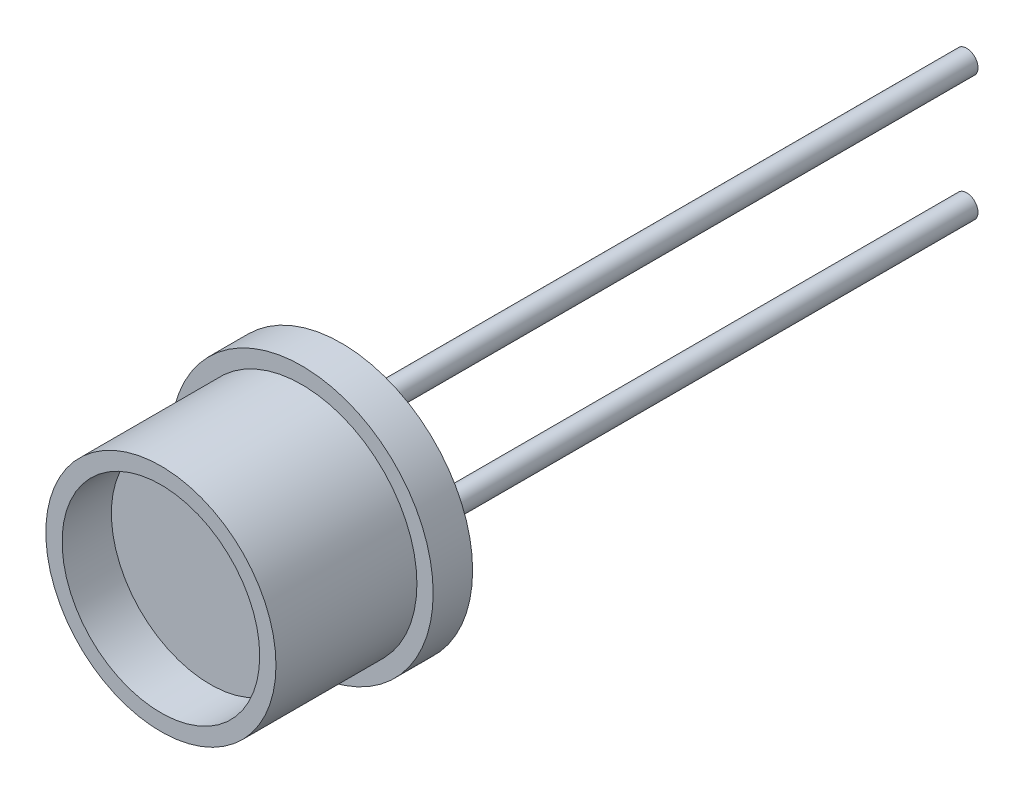
SolidWorks part; units mm, degrees
other "DetailItem1"
other "DetailItem2"
other "DetailItem3"
ref_plane "Front Plane" through (0, 0, 0) normal (0, 0, 1) x (1, 0, 0)
ref_plane "Top Plane" through (0, 0, 0) normal (0, 1, 0) x (1, 0, 0)
ref_plane "Right Plane" through (0, 0, 0) normal (1, 0, 0) x (0, 0, -1)
sketch "Sketch1" plane through (0, 0, 0) normal (0, 0, 1) x (1, 0, 0)
  circle A0 centre (0, 0) radius 2.665
  dimension "D1" = 5.33
extrude "Boss-Extrude1" add sketch "Sketch1" along normal blind 0.8
sketch "Sketch2" plane through (0, 0, 0.8) normal (0, 0, 1) x (1, 0, 0)
  circle A0 centre (0, 0) radius 2.335
  dimension "D1" = 4.67
extrude "Boss-Extrude2" add sketch "Sketch2" along normal blind 2.86
sketch "Sketch3" plane through (0, 0, 0) normal (0, 0, -1) x (-1, 0, 0)
  circle A0 centre (0, 0) radius 1.27
  circle A1 centre (0, 1.27) radius 0.23
  dimension "D1" = 2.54
  dimension "D2" = 0.46
extrude "Boss-Extrude3" add sketch "Sketch3" along normal blind 12.69 contours A1
pattern_circular "CirPattern1" count 3 every 90 about axis through (0, 0, 0) along (0, 0, 1) of "Boss-Extrude3"
sketch "Sketch4" plane through (0, 0, 3.66) normal (0, 0, 1) x (1, 0, 0)
  circle A0 centre (0, 0) radius 2.005
  dimension "D1" = 4.01
extrude "Cut-Extrude1" cut sketch "Sketch4" against normal blind 1
equation "\"D1@Boss-Extrude2\"= 3.66 - \"D1@Boss-Extrude1\""
equation "\"D1@Sketch4\"= \"D1@Sketch2\" - ( \"D1@Sketch1\" - \"D1@Sketch2\" )"
